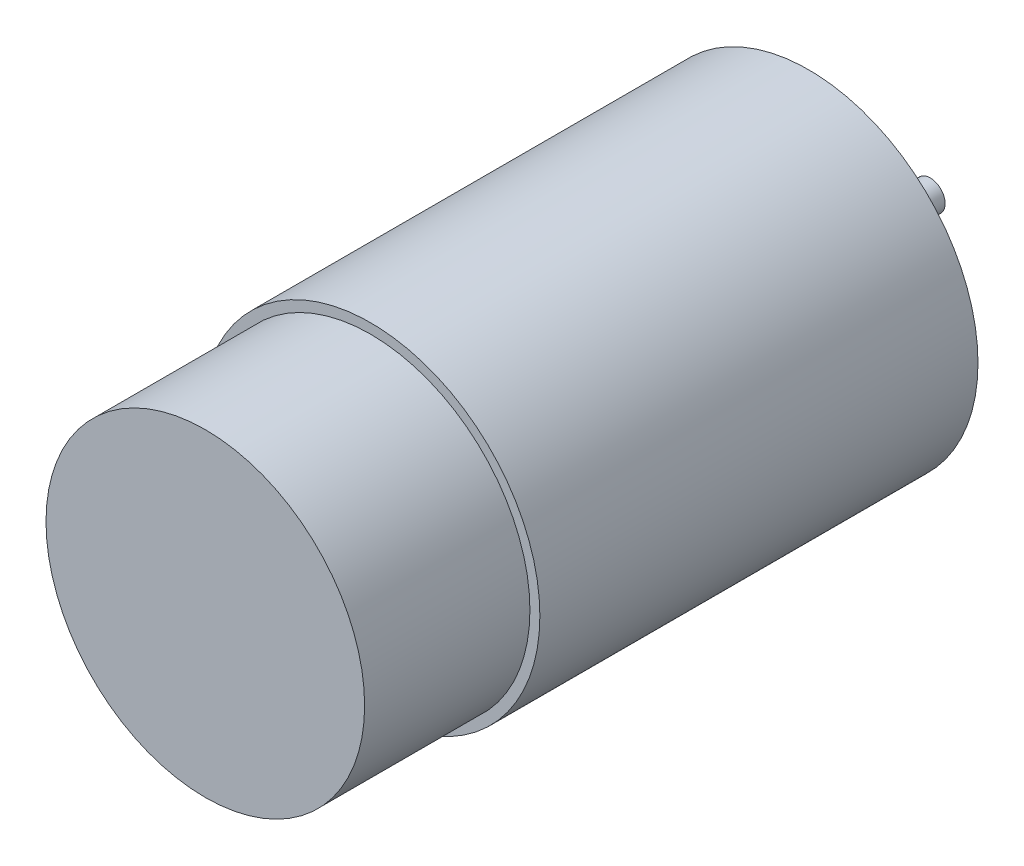
SolidWorks part; units mm, degrees
ref_plane "정면" through (0, 0, 0) normal (0, 0, 1) x (1, 0, 0)
ref_plane "윗면" through (0, 0, 0) normal (0, 1, 0) x (1, 0, 0)
ref_plane "우측면" through (0, 0, 0) normal (1, 0, 0) x (0, 0, -1)
sketch "스케치1" plane through (0, 0, 0) normal (0, 0, 1) x (1, 0, 0)
  circle A0 centre (0, 0) radius 8.5
  dimension "D1" = 17
extrude "돌출1" add sketch "스케치1" along normal blind 22
sketch "스케치2" plane through (0, 0, 22) normal (0, 0, 1) x (1, 0, 0)
  circle A0 centre (0, 0) radius 8
extrude "돌출2" add sketch "스케치2" along normal blind 8.3
sketch "스케치3" plane through (0, 0, 0) normal (0, 0, -1) x (-1, 0, 0)
  circle A0 centre (0, 0) radius 3
extrude "돌출3" add sketch "스케치3" along normal blind 1
sketch "스케치4" plane through (0, 0, -1) normal (0, 0, -1) x (-1, 0, 0)
  circle A0 centre (0, 0) radius 0.75
extrude "돌출4" add sketch "스케치4" along normal blind 5.1
